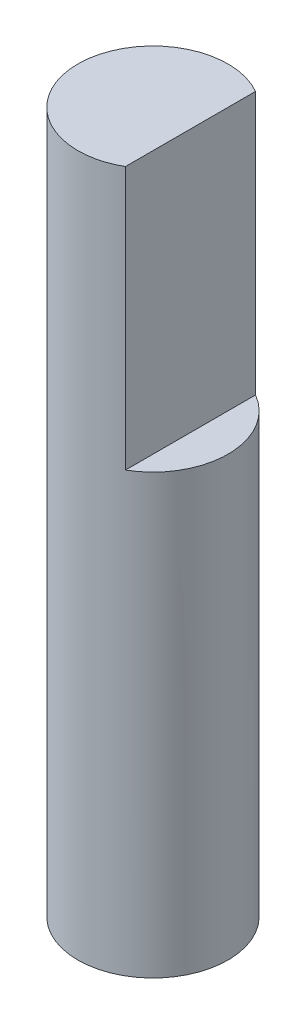
SolidWorks part; units mm, degrees
material "Chrome Stainless Steel"
ref_plane "Front Plane" through (0, 0, 0) normal (0, 0, 1) x (1, 0, 0)
ref_plane "Top Plane" through (0, 0, 0) normal (0, 1, 0) x (1, 0, 0)
ref_plane "Right Plane" through (0, 0, 0) normal (1, 0, 0) x (0, 0, -1)
sketch "Sketch1" plane through (0, 0, 0) normal (0, 1, 0) x (1, 0, 0)
  circle A0 centre (0, 0) radius 3
  dimension "D1" = 6
extrude "Boss-Extrude1" add sketch "Sketch1" along normal blind 18 and the other way blind 10
sketch "Sketch2" plane through (0, 18, 0) normal (0, 1, 0) x (1, 0, 0)
  line L0 (0, 0) -> (1.5, 0) construction
  line L1 (1.5, 3) -> (3, 3)
  line L2 (1.5, 3) -> (1.5, -3)
  line L3 (1.5, -3) -> (3, -3)
  line L4 (3, 3) -> (3, -3)
  circle A0 centre (0, 0) radius 3 construction
  dimension "D1" = 1.5
  dimension "D2" = 6
extrude "Cut-Extrude1" cut sketch "Sketch2" against normal blind 10.5
